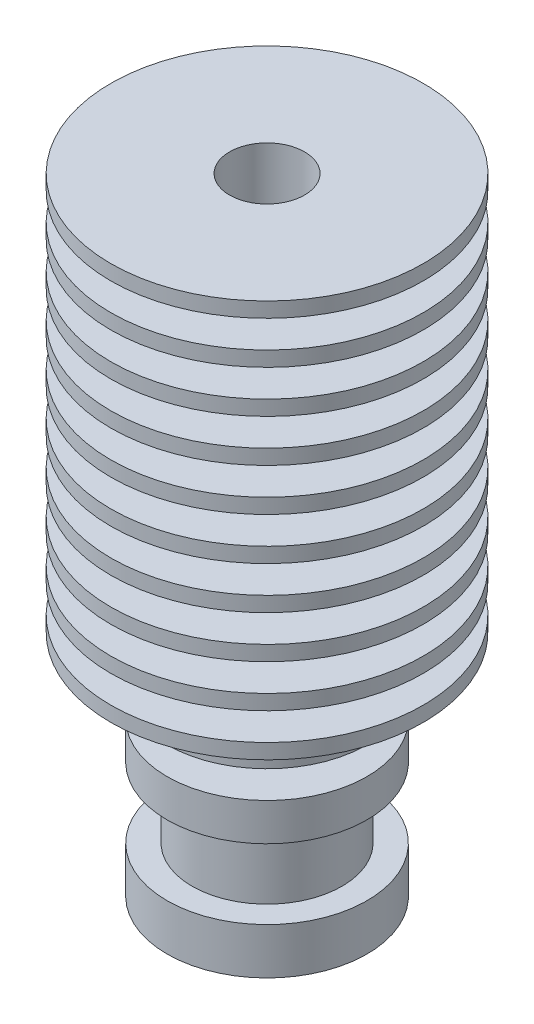
SolidWorks part; units mm, degrees
ref_plane "Front Plane" through (0, 0, 0) normal (0, 0, 1) x (1, 0, 0)
ref_plane "Top Plane" through (0, 0, 0) normal (0, 1, 0) x (1, 0, 0)
ref_plane "Right Plane" through (0, 0, 0) normal (1, 0, 0) x (0, 0, -1)
sketch "Sketch1" plane through (0, 0, 0) normal (0, 0, 1) x (1, 0, 0)
  line L0 (0, 0) -> (8, 0)
  line L1 (8, 0) -> (8, 3.7)
  line L2 (8, 3.7) -> (6, 3.7)
  line L3 (6, 3.7) -> (6, 9.3)
  line L4 (6, 9.3) -> (8, 9.3)
  line L5 (8, 9.3) -> (8, 12.3)
  line L6 (8, 12.3) -> (4.5, 12.3)
  line L7 (4.5, 12.3) -> (4.5, 14.5)
  line L8 (4.5, 14.5) -> (8, 14.5)
  line L9 (8, 14.5) -> (8, 16.1)
  line L10 (8, 16.1) -> (4.5, 16.1)
  line L11 (4.5, 16.1) -> (4.5, 18.3)
  line L12 (4.5, 18.3) -> (12.5, 18.3)
  line L13 (12.5, 18.3) -> (12.5, 19.5)
  line L14 (12.5, 19.5) -> (4.5, 19.5)
  line L15 (4.5, 19.5) -> (4.5, 21.7)
  line L16 (4.5, 21.7) -> (12.5, 21.7)
  line L17 (12.5, 21.7) -> (12.5, 22.9)
  line L18 (12.5, 22.9) -> (4.5, 22.9)
  line L19 (4.5, 22.9) -> (4.5, 25.1)
  line L20 (4.5, 25.1) -> (12.5, 25.1)
  line L21 (12.5, 25.1) -> (12.5, 26.3)
  line L22 (12.5, 26.3) -> (4.5, 26.3)
  line L23 (4.5, 26.3) -> (4.5, 28.5)
  line L24 (4.5, 28.5) -> (12.5, 28.5)
  line L25 (12.5, 28.5) -> (12.5, 29.7)
  line L26 (12.5, 29.7) -> (6.5, 29.7)
  line L27 (6.5, 29.7) -> (6.5, 31.9)
  line L28 (6.5, 31.9) -> (12.5, 31.9)
  line L29 (12.5, 31.9) -> (12.5, 33.1)
  line L30 (12.5, 33.1) -> (7.5, 33.1)
  line L31 (7.5, 33.1) -> (7.5, 35.3)
  line L32 (7.5, 35.3) -> (12.5, 35.3)
  line L33 (12.5, 35.3) -> (12.5, 36.5)
  line L34 (12.5, 36.5) -> (7.5, 36.5)
  line L35 (7.5, 36.5) -> (7.5, 38.7)
  line L36 (7.5, 38.7) -> (12.5, 38.7)
  line L37 (12.5, 38.7) -> (12.5, 39.9)
  line L38 (12.5, 39.9) -> (7.5, 39.9)
  line L39 (7.5, 39.9) -> (7.5, 42.1)
  line L40 (7.5, 42.1) -> (12.5, 42.1)
  line L41 (12.5, 42.1) -> (12.5, 43.3)
  line L42 (12.5, 43.3) -> (7.5, 43.3)
  line L43 (7.5, 43.3) -> (7.5, 45.5)
  line L44 (7.5, 45.5) -> (12.5, 45.5)
  line L45 (12.5, 45.5) -> (12.5, 46.7)
  line L46 (12.5, 46.7) -> (7.5, 46.7)
  line L47 (7.5, 46.7) -> (7.5, 48.9)
  line L48 (7.5, 48.9) -> (12.5, 48.9)
  line L49 (12.5, 48.9) -> (12.5, 50.1)
  line L50 (12.5, 50.1) -> (9.2007, 50.1)
  line L51 (9.2007, 50.1) -> (0, 50.1)
  line L52 (0, 50.1) -> (0, 0)
  dimension "D1" = 8
  dimension "D2" = 3.7
  dimension "D3" = 2
  dimension "D4" = 12.3
  dimension "D5" = 9.3
  dimension "D6" = 4.5
  dimension "D7" = 14.5
  dimension "D8" = 18.3
  dimension "D9" = 3.4
  dimension "D10" = 2.2
  dimension "D11" = 31.8
  dimension "D12" = 50.1
  dimension "D13" = 12.5
  dimension "D14" = 6.5
  dimension "D15" = 7.5
revolve "Revolve1" add sketch "Sketch1" angle 360 about L52
sketch "Sketch2" plane through (0, 0, 0) normal (0, 0, 1) x (1, 0, 0)
  line L0 (3.2, 0) -> (3.2, 10)
  line L1 (0, 0) -> (8, 0) construction
  line L2 (3.2, 10) -> (1.8721, 12.3)
  line L3 (8, 12.3) -> (4.5, 12.3) construction
  line L4 (1.8721, 12.3) -> (1.8721, 18.3)
  line L5 (1.8721, 18.3) -> (1, 19.5)
  line L6 (1, 19.5) -> (1, 32.1)
  line L7 (0, 50.1) -> (0, 0) construction
  line L8 (12.5, 19.5) -> (4.5, 19.5) construction
  line L9 (3, 50.1) -> (3, 32.7351)
  line L10 (9.2007, 50.1) -> (0, 50.1) construction
  line L11 (1, 32.1) -> (1.9, 32.1)
  line L12 (7.5, 33.1) -> (7.5, 35.3) construction
  line L13 (3, 50.1) -> (0, 50.1)
  line L14 (0, 50.1) -> (0, 0)
  line L15 (0, 0) -> (3.2, 0)
  line L16 (1.9, 32.1) -> (3, 32.7351)
  point P19 (7.5, 34.2)
  dimension "D1" = 3.2
  dimension "D2" = 10
  dimension "D3" = 30
  dimension "D4" = 6
  dimension "D5" = 1
  dimension "D6" = 3
  dimension "D7" = 150
  dimension "D8" = 1.9
  dimension "D9" = 18
revolve "Cut-Revolve2" cut sketch "Sketch2" angle 360 about L52
equation "\"D1@Sketch1\"=16/2"
equation "\"D3@Sketch1\"=(16-12)/2"
equation "\"D6@Sketch1\"=9/2"
equation "\"D1@Sketch2\"=6.4/2"
equation "\"D5@Sketch2\"=2/2"
equation "\"D6@Sketch2\"=6/2"
equation "\"D8@Sketch2\"=3.8/2"
equation "\"D14@Sketch1\"=13/2"
equation "\"D15@Sketch1\"=15/2"
equation "\"D13@Sketch1\"=25/2"
